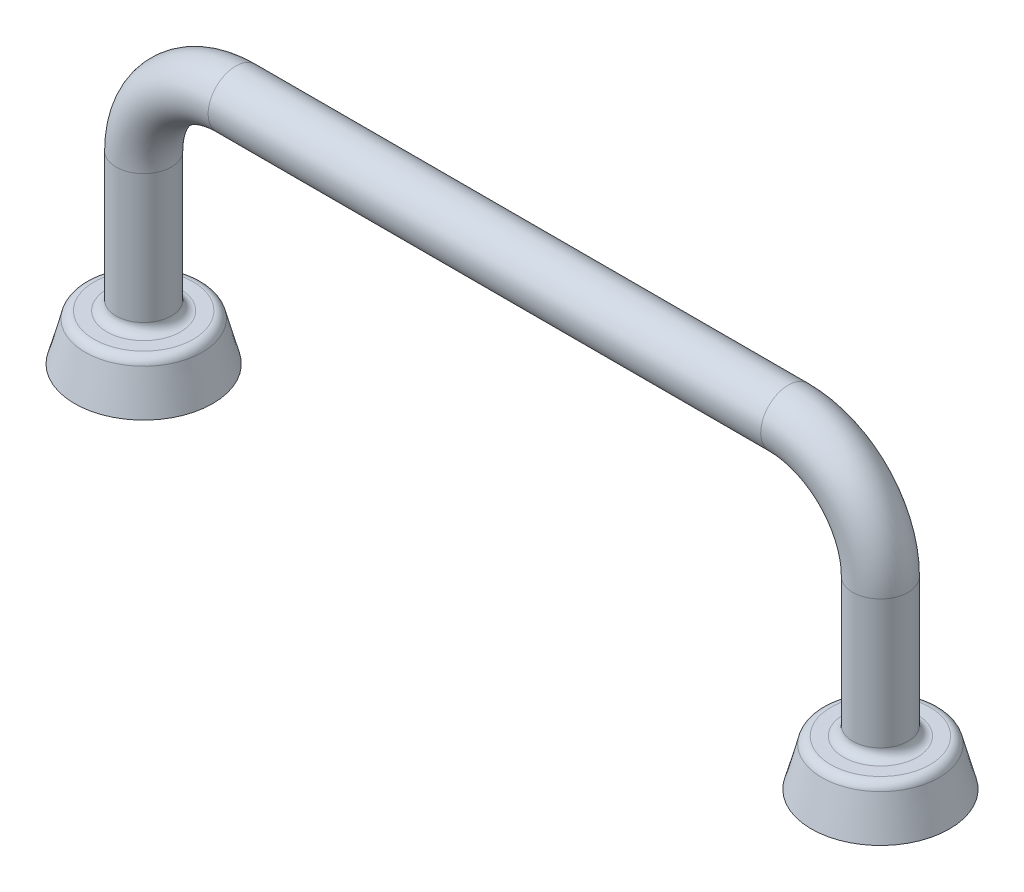
SolidWorks part; units mm, degrees
ref_plane "Front Plane" through (0, 0, 0) normal (0, 0, 1) x (1, 0, 0)
ref_plane "Top Plane" through (0, 0, 0) normal (0, 1, 0) x (1, 0, 0)
ref_plane "Right Plane" through (0, 0, 0) normal (1, 0, 0) x (0, 0, -1)
sketch "Sketch1" plane through (0, 0, 0) normal (0, 0, 1) x (1, 0, 0)
  line L0 (0, 0) -> (0, 20)
  line L1 (-10, 30) -> (-70, 30)
  line L2 (-80, 20) -> (-80, 0)
  arc A0 (-10, 30) -> (0, 20) centre (-10, 20) cw
  arc A1 (-80, 20) -> (-70, 30) centre (-70, 20) cw
  dimension "D1" = 10
  dimension "D2" = 80
  dimension "D3" = 30
sweep "Sweep1" add path "Sketch1" circular profile diameter 6 parameters "D3"=6
sketch "Sketch10" plane through (0, 0, 0) normal (0, -1, 0) x (1, 0, 0)
  circle A0 centre (-80, 0) radius 7.5
  circle A1 centre (0, 0) radius 7.5
  dimension "D1" = 15
extrude "Boss-Extrude1" add sketch "Sketch10" against normal blind 5 draft 15
fillet "Fillet2" radius 1 4 edges at (-73.8397, 5, 0) (-77, 5, 0) (6.1603, 5, 0) (3, 5, 0)
hole_wizard "M5x0.8 Tapped Hole1" positions "Sketch15" profile "Sketch17" tap size "M5x0.8" standard "ANSI Metric"
sketch "Sketch15" plane through (0, 0, 0) normal (0, -1, 0) x (-1, 0, 0)
  point P0 (80, 0)
  point P3 (0, 0)
sketch "Sketch17" plane through (-80, 0, 0) normal (1, 0, 0) x (0, 0, -1)
  line L0 (0, 0) -> (0, 11.2618)
  line L1 (0, 11.2618) -> (2.1, 10)
  line L2 (2.1, 10) -> (2.1, 0)
  line L5 (2.1, 0) -> (0, 0)
  line L10 (0, 11.2618) -> (-2.1, 10) construction
  line L11 (0, -6.35) -> (0, 107.95) construction
  dimension "Tap Drill Dia." = 4.2
  dimension "Tap Drill Depth" = 10
  dimension "Drill Angle" = 118
cosmetic thread "Hole Thread1" parameters "D1"=10, "D2"=5
cosmetic thread "Hole Thread2" parameters "D1"=10, "D2"=5
chamfer "Chamfer1" distance 0.5 angle 45 2 edges at (0, 0, -2.1) (-80, 0, -2.1)
